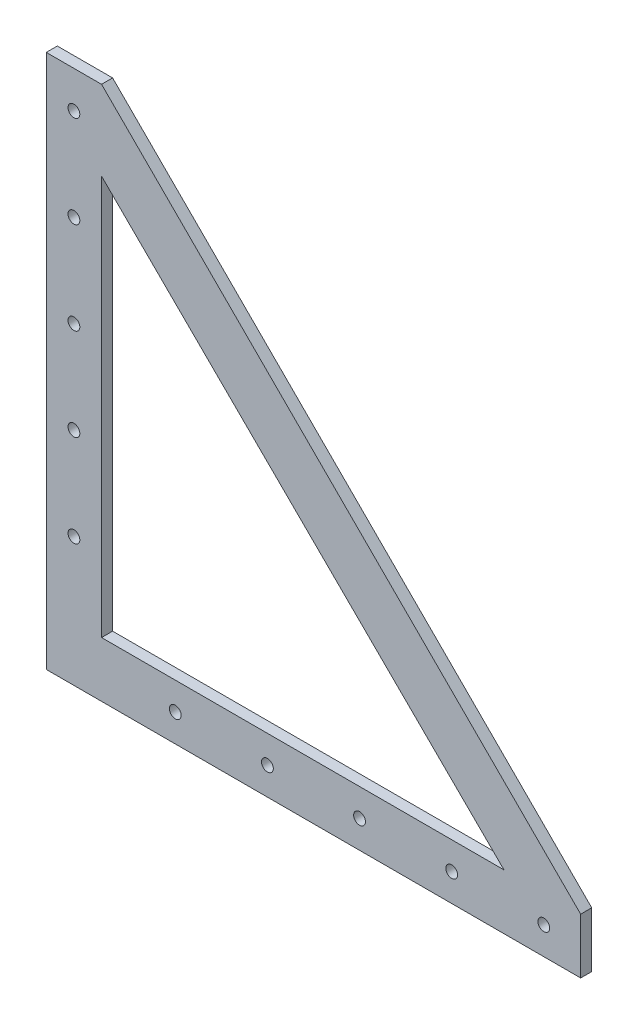
SolidWorks part; units mm, degrees
ref_plane "Front Plane" through (0, 0, 0) normal (0, 0, 1) x (1, 0, 0)
ref_plane "Top Plane" through (0, 0, 0) normal (0, 1, 0) x (1, 0, 0)
ref_plane "Right Plane" through (0, 0, 0) normal (1, 0, 0) x (0, 0, -1)
sketch "Sketch1" plane through (0, 0, 0) normal (0, 0, 1) x (1, 0, 0)
  line L0 (0, 145) -> (0, 0)
  line L1 (0, 0) -> (145, 0)
  line L2 (145, 0) -> (145, 15)
  line L3 (145, 15) -> (15, 145)
  line L4 (15, 145) -> (0, 145)
  line L5 (145, 7.5) -> (0, 7.5) construction
  line L6 (7.5, 145) -> (7.5, 7.5) construction
  line L7 (15, 123.4185) -> (15, 15)
  line L8 (15, 15) -> (124.2033, 15)
  line L9 (124.2033, 15) -> (15, 123.4185)
  line L10 (15, 92.0793) -> (0, 92.0793) construction
  line L11 (47.2055, 15) -> (47.2055, 0) construction
  line L12 (66.2437, 72.5431) -> (76.8503, 83.1497) construction
  circle A0 centre (135, 7.5) radius 1.6
  circle A1 centre (110, 7.5) radius 1.6
  circle A2 centre (85, 7.5) radius 1.6
  circle A3 centre (60, 7.5) radius 1.6
  circle A4 centre (35, 7.5) radius 1.6
  circle A5 centre (7.5, 135) radius 1.6
  circle A6 centre (7.5, 110) radius 1.6
  circle A7 centre (7.5, 85) radius 1.6
  circle A8 centre (7.5, 60) radius 1.6
  circle A9 centre (7.5, 35) radius 1.6
  dimension "D4" = 3.2
  dimension "D7" = 3.2
  dimension "D1" = 15
  dimension "D2" = 145
  dimension "D3" = 145
  dimension "D5" = 10
  dimension "D8" = 10
  dimension "D6" = 5
  dimension "D9" = 5
extrude "Boss-Extrude1" add sketch "Sketch1" along normal blind 3
